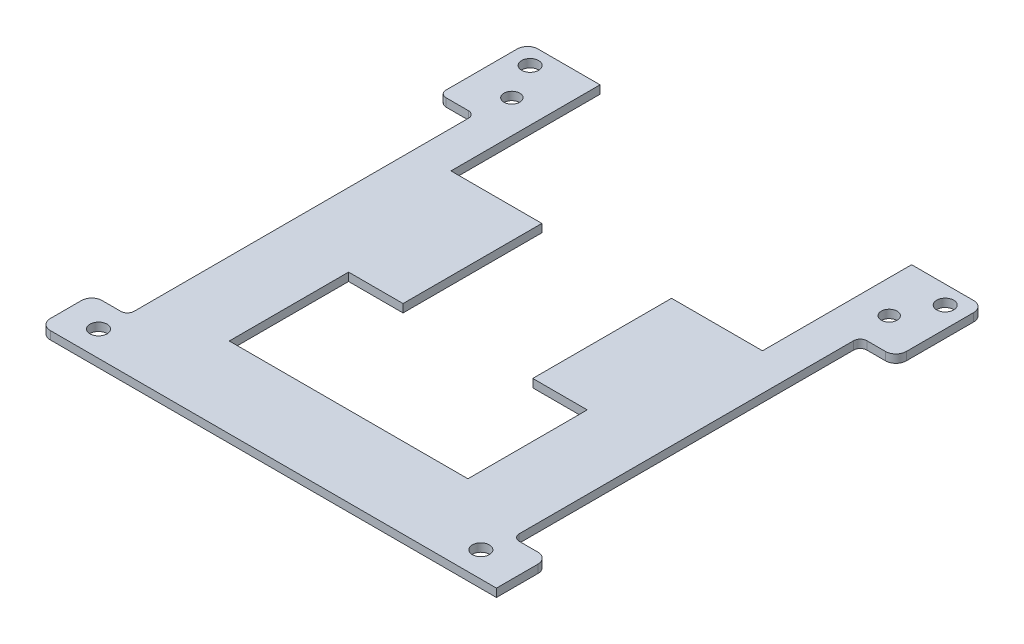
SolidWorks part; units mm, degrees
material "Copper"
ref_plane "Front Plane" through (0, 0, 0) normal (0, 0, 1) x (1, 0, 0)
ref_plane "Top Plane" through (0, 0, 0) normal (0, 1, 0) x (1, 0, 0)
ref_plane "Right Plane" through (0, 0, 0) normal (1, 0, 0) x (0, 0, -1)
sketch "Sketch1" plane through (0, 0, 0) normal (0, 1, 0) x (1, 0, 0)
  line L0 (-38.395, 30) -> (-42.73, 30)
  line L1 (-44, 31.27) -> (-44, 45)
  line L2 (-42, 47) -> (42, 47)
  line L3 (44, 45) -> (44, 32)
  line L4 (42, 30) -> (38.395, 30)
  line L5 (37.125, 28.73) -> (37.125, -35.73)
  line L6 (38.395, -37) -> (42, -37)
  line L7 (44, -39) -> (44, -47)
  line L8 (44, -47) -> (-42, -47)
  line L9 (-44, -45) -> (-44, -38.977)
  line L10 (-42, -37) -> (-38.395, -37)
  line L11 (-37.125, -35.73) -> (-37.125, 28.73)
  line L12 (23, -31.5) -> (-23, -31.5)
  line L13 (-23, -31.5) -> (-23, -8.5)
  line L14 (-23, -8.5) -> (-12.5, -8.5)
  line L15 (-12.5, -8.5) -> (-12.5, 35)
  line L16 (-12.5, 35) -> (12.5, 35)
  line L17 (12.5, 35) -> (12.5, -8.5)
  line L18 (12.5, -8.5) -> (23, -8.5)
  line L19 (23, -8.5) -> (23, -31.5)
  circle A0 centre (40, 43.5) radius 1.6383
  circle A1 centre (-40, 43.5) radius 1.6383
  circle A2 centre (-37.6, -42.1) radius 1.6383
  circle A3 centre (36.1, -42.1) radius 1.6383
  arc A4 (-44, 31.27) -> (-42.73, 30) centre (-42.73, 31.27) ccw
  arc A5 (-42, 47) -> (-44, 45) centre (-42, 45) ccw
  arc A6 (44, 45) -> (42, 47) centre (42, 45) ccw
  arc A7 (42, 30) -> (44, 32) centre (42, 32) ccw
  arc A8 (38.395, 30) -> (37.125, 28.73) centre (38.395, 28.73) ccw
  arc A9 (37.125, -35.73) -> (38.395, -37) centre (38.395, -35.73) ccw
  arc A10 (44, -39) -> (42, -37) centre (42, -39) ccw
  arc A11 (-44, -45) -> (-42, -47) centre (-42, -45) ccw
  arc A12 (-42, -37) -> (-44, -38.977) centre (-42.0115, -38.9885) ccw
  arc A13 (-38.395, -37) -> (-37.125, -35.73) centre (-38.395, -35.73) ccw
  arc A14 (-37.125, 28.73) -> (-38.395, 30) centre (-38.395, 28.73) ccw
extrude "Boss-Extrude1" add sketch "Sketch1" along normal blind 1.575
sketch "Sketch2" plane through (0, 1.575, 0) normal (0, 1, 0) x (1, 0, 0)
  line L0 (-12.5, 18.2554) -> (-30.026, 18.2554)
  line L1 (42, 47) -> (-42, 47) construction
  line L2 (-12.5, 35) -> (12.5, 35) construction
  line L3 (-30.026, 47) -> (30.026, 47)
  line L4 (12.5, -8.5) -> (12.5, 35) construction
  line L5 (12.5, 18.2554) -> (30.026, 18.2554)
  line L6 (30.026, 18.2554) -> (30.026, 47)
  line L7 (0, 47) -> (0, -47) construction
  line L8 (-42, -47) -> (44, -47) construction
  line L9 (-12.5, 35) -> (-12.5, 18.2554)
  line L10 (-30.026, 18.2554) -> (-30.026, 47)
  line L11 (12.5, 35) -> (12.5, 18.2554)
  line L13 (-12.5, 35) -> (12.5, 35)
  dimension "D2" = 17.526
extrude "Cut-Extrude1" cut sketch "Sketch2" against normal blind 2.54
sketch "Sketch15" plane through (0, 1.575, 0) normal (0, 1, 0) x (1, 0, 0)
  line L0 (-30.026, 47) -> (-30.026, 18.2554) construction
  line L4 (42, 47) -> (30.026, 47) construction
  line L5 (30.026, 18.2554) -> (30.026, 47) construction
  circle A0 centre (-36.376, 36.35) radius 1.524
  circle A1 centre (36.376, 36.332) radius 1.524
  dimension "D1" = 3.048
  dimension "D3" = 3.048
  dimension "D4" = 10.668
  dimension "D2" = 6.35
  dimension "D5" = 6.35
extrude "Cut-Extrude5" cut sketch "Sketch15" against normal blind 1.575
